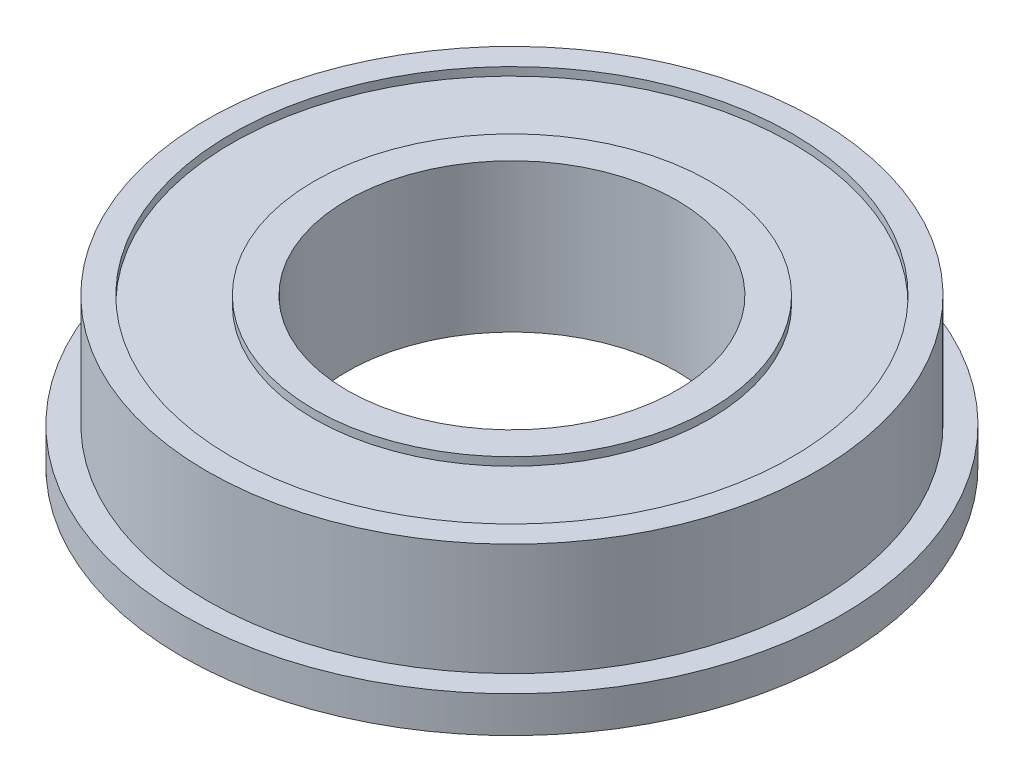
SolidWorks part; units mm, degrees
ref_plane "前视基准面" through (0, 0, 0) normal (0, 0, 1) x (1, 0, 0)
ref_plane "上视基准面" through (0, 0, 0) normal (0, 1, 0) x (1, 0, 0)
ref_plane "右视基准面" through (0, 0, 0) normal (1, 0, 0) x (0, 0, -1)
sketch "草图1" plane through (0, 0, 0) normal (0, 1, 0) x (1, 0, 0)
  circle A0 centre (0, 0) radius 20
  dimension "D1" = 40
extrude "凸台-拉伸1" add sketch "草图1" along normal blind 2.2
sketch "草图2" plane through (0, 2.2, 0) normal (0, 1, 0) x (1, 0, 0)
  circle A0 centre (0, 0) radius 18.5
  dimension "D1" = 37
extrude "凸台-拉伸2" add sketch "草图2" along normal blind 6.8
sketch "草图3" plane through (0, 9, 0) normal (0, 1, 0) x (1, 0, 0)
  circle A0 centre (0, 0) radius 10
  dimension "D1" = 20
extrude "切除-拉伸1" cut sketch "草图3" against normal blind 9
sketch "草图4" plane through (0, 0, 0) normal (0, -1, 0) x (1, 0, 0)
  circle A0 centre (0, 0) radius 12
  circle A1 centre (0, 0) radius 17
  dimension "D1" = 24
  dimension "D2" = 34
extrude "切除-拉伸2" cut sketch "草图4" against normal blind 0.5
sketch "草图5" plane through (0, 9, 0) normal (0, 1, 0) x (1, 0, 0)
  circle A0 centre (0, 0) radius 12
  circle A1 centre (0, 0) radius 17
  dimension "D1" = 24
  dimension "D2" = 34
extrude "切除-拉伸3" cut sketch "草图5" against normal blind 0.5
